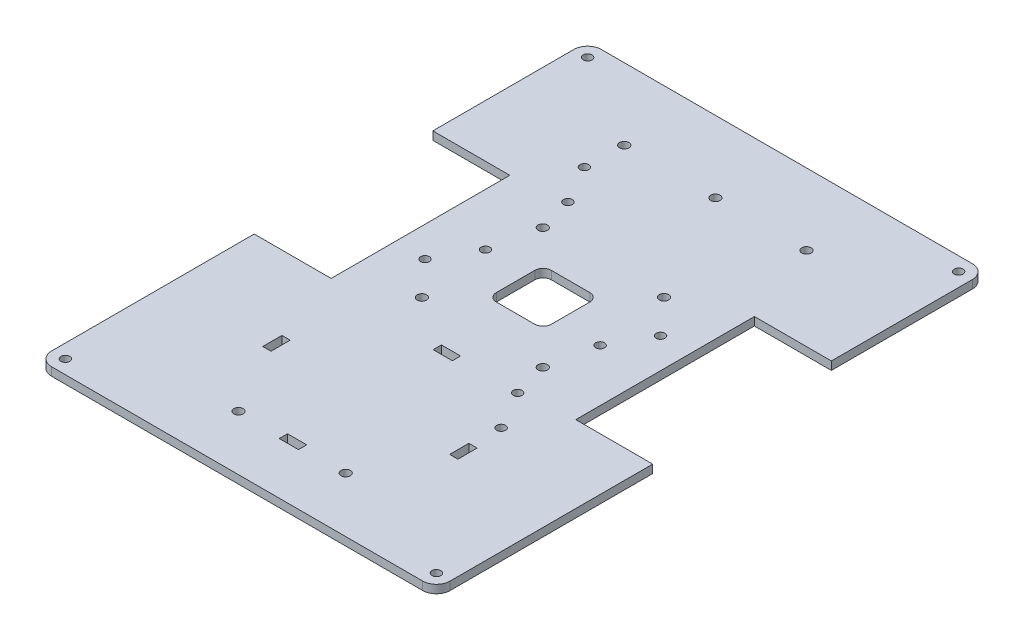
SolidWorks part; units mm, degrees
ref_plane "前视基准面" through (0, 0, 0) normal (0, 0, 1) x (1, 0, 0)
ref_plane "上视基准面" through (0, 0, 0) normal (0, 1, 0) x (1, 0, 0)
ref_plane "右视基准面" through (0, 0, 0) normal (1, 0, 0) x (0, 0, -1)
other "Configuration Table"
sketch "草图1" plane through (0, 0, 0) normal (0, 1, 0) x (1, 0, 0)
  line L0 (-42.7, 30.85) -> (-22, 30.85) construction
  line L1 (-67.5, 100) -> (67.5, 100)
  line L2 (-72.5, 95) -> (-72.5, -95)
  line L3 (-67.5, -100) -> (67.5, -100)
  line L4 (72.5, 95) -> (72.5, -95)
  line L5 (-72.5, 100) -> (72.5, -100) construction
  line L6 (-72.5, -100) -> (72.5, 100) construction
  line L7 (-42.7, 63) -> (-22, 63) construction
  line L8 (-42.7, 63) -> (-42.7, -1.3) construction
  line L9 (-42.7, -1.3) -> (-22, -1.3) construction
  line L10 (-22, 63) -> (-22, -1.3) construction
  line L11 (44.5, 43.7) -> (44.5, -21.3)
  line L12 (-44.5, -21.3) -> (-72.5, -21.3)
  line L13 (-44.5, -21.3) -> (-44.5, 43.7)
  line L14 (-44.5, 43.7) -> (-72.5, 43.7)
  line L15 (-72.5, -21.3) -> (-72.5, 43.7)
  line L16 (-44.5, -21.3) -> (-72.5, 43.7) construction
  line L17 (-44.5, 43.7) -> (-72.5, -21.3) construction
  line L23 (-45.15, 63) -> (45.15, 63) construction
  line L24 (-45.15, 63) -> (-45.15, 100) construction
  line L25 (-45.15, 100) -> (45.15, 100) construction
  line L26 (45.15, 63) -> (45.15, 100) construction
  line L27 (-45.15, 63) -> (45.15, 100) construction
  line L28 (-45.15, 100) -> (45.15, 63) construction
  line L29 (-22, -10.6916) -> (22, -10.6916) construction
  line L30 (-22, -10.6916) -> (-22, 33.3084) construction
  line L31 (-22, 33.3084) -> (22, 33.3084) construction
  line L32 (22, -10.6916) -> (22, 33.3084) construction
  line L33 (-22, -10.6916) -> (22, 33.3084) construction
  line L34 (-22, 33.3084) -> (22, -10.6916) construction
  line L43 (-7, 21.3084) -> (7, 21.3084)
  line L44 (-10, 18.3084) -> (-10, 4.3084)
  line L45 (-7, 1.3084) -> (7, 1.3084)
  line L46 (10, 18.3084) -> (10, 4.3084)
  line L47 (-10, 21.3084) -> (10, 1.3084) construction
  line L48 (-10, 1.3084) -> (10, 21.3084) construction
  line L49 (44.5, 43.7) -> (72.5, 43.7)
  line L50 (72.5, 43.7) -> (72.5, -21.3)
  line L51 (44.5, -21.3) -> (72.5, -21.3)
  line L53 (34, -79.6916) -> (-34, -79.6916) construction
  line L54 (34, -79.6916) -> (34, -23.6916) construction
  line L55 (34, -23.6916) -> (-34, -23.6916) construction
  line L56 (-34, -79.6916) -> (-34, -23.6916) construction
  line L57 (34, -79.6916) -> (-34, -23.6916) construction
  line L58 (34, -23.6916) -> (-34, -79.6916) construction
  line L59 (-3.5, -25.1916) -> (3.5, -25.1916)
  line L60 (-3.5, -25.1916) -> (-3.5, -22.1916)
  line L61 (-3.5, -22.1916) -> (3.5, -22.1916)
  line L62 (3.5, -25.1916) -> (3.5, -22.1916)
  line L63 (-3.5, -25.1916) -> (3.5, -22.1916) construction
  line L64 (-3.5, -22.1916) -> (3.5, -25.1916) construction
  line L65 (-35.5, -48.1916) -> (-32.5, -48.1916)
  line L66 (-35.5, -48.1916) -> (-35.5, -55.1916)
  line L67 (-35.5, -55.1916) -> (-32.5, -55.1916)
  line L68 (-32.5, -48.1916) -> (-32.5, -55.1916)
  line L69 (-35.5, -48.1916) -> (-32.5, -55.1916) construction
  line L70 (-35.5, -55.1916) -> (-32.5, -48.1916) construction
  line L78 (32.5, -55.1916) -> (32.5, -48.1916)
  line L79 (35.5, -55.1916) -> (32.5, -55.1916)
  line L80 (35.5, -55.1916) -> (35.5, -48.1916)
  line L81 (35.5, -48.1916) -> (32.5, -48.1916)
  line L82 (3.5, -78.1916) -> (-3.5, -78.1916)
  line L83 (3.5, -81.1916) -> (-3.5, -81.1916)
  line L84 (3.5, -78.1916) -> (3.5, -81.1916)
  line L85 (-3.5, -78.1916) -> (-3.5, -81.1916)
  circle A0 centre (-33.5, 59.85) radius 1.6
  circle A1 centre (-25.5, 45.85) radius 1.6
  circle A4 centre (-25.5, 15.85) radius 1.6
  circle A5 centre (-33.5, 1.85) radius 1.6
  circle A10 centre (0, 74) radius 1.7
  circle A11 centre (33.15, 74) radius 1.7
  circle A12 centre (-33.15, 74) radius 1.7
  circle A13 centre (-67.5, 95) radius 1.6
  circle A14 centre (67.5, 95) radius 1.6
  circle A15 centre (67.5, -95) radius 1.6
  circle A16 centre (-67.5, -95) radius 1.6
  circle A18 centre (-22, 33.2) radius 1.7
  circle A19 centre (-22, -10.8) radius 1.7
  circle A20 centre (22, -10.8) radius 1.7
  circle A21 centre (22, 33.3084) radius 1.7
  circle A22 centre (33.5, -37.45) radius 1.6
  circle A23 centre (25.5, -23.45) radius 1.6
  circle A24 centre (25.5, 6.55) radius 1.6
  circle A25 centre (33.5, 20.55) radius 1.6
  circle A26 centre (-19.5, -80) radius 1.7
  circle A27 centre (19.5, -80) radius 1.7
  arc A28 (-10, 18.3084) -> (-7, 21.3084) centre (-7, 18.3084) cw
  arc A29 (10, 4.3084) -> (7, 1.3084) centre (7, 4.3084) cw
  arc A30 (-10, 4.3084) -> (-7, 1.3084) centre (-7, 4.3084) ccw
  arc A31 (10, 18.3084) -> (7, 21.3084) centre (7, 18.3084) ccw
  arc A32 (-67.5, 100) -> (-72.5, 95) centre (-67.5, 95) ccw
  arc A33 (72.5, 95) -> (67.5, 100) centre (67.5, 95) ccw
  arc A34 (67.5, -100) -> (72.5, -95) centre (67.5, -95) ccw
  arc A35 (-67.5, -100) -> (-72.5, -95) centre (-67.5, -95) cw
  point P0 (0, 0)
  point P21 (-58.5, 11.2)
  point P26 (0, 11.3084)
  point P28 (0, 11.2)
  point P29 (0, 81.5)
  point P42 (-0.0125, 11.2023)
  point P54 (0, 11.3084)
  point P77 (0, 11.2)
  point P80 (-34, -51.6916)
  point P81 (0, -51.6916)
  point P83 (0, 11.2)
  point P87 (0, -23.6916)
  point P97 (0, 0)
  point P106 (0, -51.6916)
  dimension "D5" = 15
  dimension "D17" = 12
  dimension "D19" = 12
  dimension "D21" = 5
  dimension "D26" = 2
  dimension "D14" = 20
  dimension "D27" = 39
  dimension "D40" = 3
  dimension "D41" = 3
  dimension "D42" = 3
  dimension "D43" = 3
  dimension "D44" = 5
  dimension "D45" = 5
  dimension "D46" = 5
  dimension "D47" = 5
  dimension "D1" = 145
  dimension "D2" = 200
  dimension "D3" = 20.7
  dimension "D4" = 64.3
  dimension "D6" = 29
  dimension "D7" = 8
  dimension "D8" = 9.2
  dimension "D9" = 29.8
  dimension "D10" = 65
  dimension "D11" = 28
  dimension "D12" = 12.5
  dimension "D13" = 37
  dimension "D15" = 90.3
  dimension "D16" = 37
  dimension "D18" = 11
  dimension "D20" = 11
  dimension "D22" = 5
  dimension "D23" = 2
  dimension "D25" = 44
  dimension "D28" = 20
  dimension "D29" = 53
  dimension "D30" = 68
  dimension "D31" = 56
  dimension "D32" = 13
  dimension "D33" = 7
  dimension "D34" = 3
  dimension "D35" = 7
  dimension "D36" = 3
  dimension "D38" = 56.3
  dimension "D39" = 28
  dimension "D24" = 2
  dimension "D37" = 2
extrude "凸台-拉伸2" add sketch "草图1" along normal blind 3
